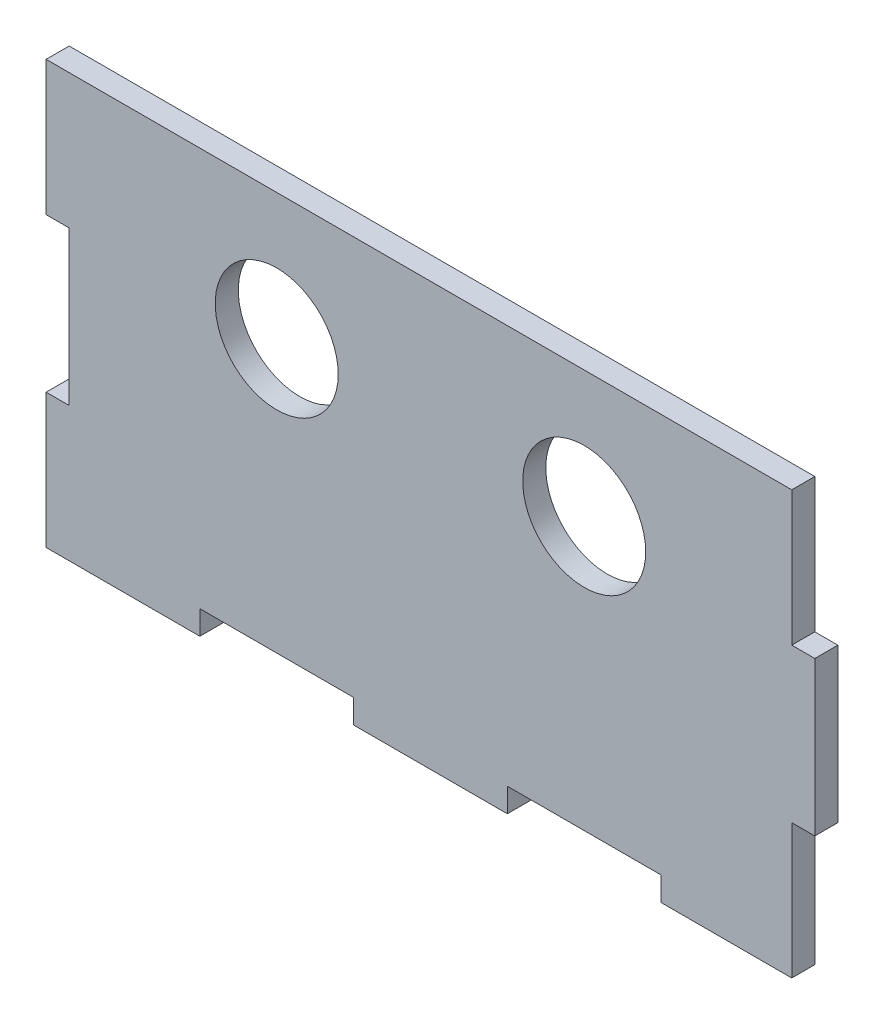
SolidWorks part; units mm, degrees
ref_plane "Front Plane" through (0, 0, 0) normal (0, 0, 1) x (1, 0, 0)
ref_plane "Top Plane" through (0, 0, 0) normal (0, 1, 0) x (1, 0, 0)
ref_plane "Right Plane" through (0, 0, 0) normal (1, 0, 0) x (0, 0, -1)
sketch "Sketch1" plane through (0, 0, 0) normal (0, 0, 1) x (1, 0, 0)
  line L0 (-50, -27.5) -> (-50, -10)
  line L1 (-50, -27.5) -> (50, -27.5)
  line L2 (-50, -27.5) -> (-50, 27.5)
  line L3 (-50, 27.5) -> (50, 27.5)
  line L4 (50, -27.5) -> (50, 27.5)
  line L5 (-50, -27.5) -> (50, 27.5) construction
  line L6 (-50, 27.5) -> (50, -27.5) construction
  line L7 (-50, -10) -> (-47, -10)
  line L8 (-47, -10) -> (-47, 10)
  line L9 (-47, 10) -> (-50, 10)
  line L10 (-50, 10) -> (-50, 27.5)
  line L11 (50, -10) -> (47, -10)
  line L12 (47, -10) -> (47, -27.5)
  line L13 (50, 10) -> (47, 10)
  line L14 (47, 10) -> (47, 27.5)
  line L15 (-50, -27.5) -> (-30, -27.5)
  line L16 (-30, -27.5) -> (-30, -24.3935)
  line L17 (-30, -24.3935) -> (-10, -24.3935)
  line L18 (-10, -24.3935) -> (-10, -27.5)
  line L19 (-10, -27.5) -> (10, -27.5)
  line L20 (10, -27.5) -> (10, -24.3935)
  line L21 (10, -24.3935) -> (30, -24.3935)
  line L22 (30, -24.3935) -> (30, -27.5)
  circle A0 centre (-20, 11) radius 8
  circle A1 centre (20, 11) radius 8
  point P0 (0, 0)
  dimension "D12" = 16
  dimension "D15" = 16
  dimension "D1" = 55
  dimension "D2" = 17.5
  dimension "D3" = 17.5
  dimension "D4" = 3
  dimension "D5" = 3
  dimension "D6" = 3
  dimension "D7" = 100
  dimension "D8" = 20
  dimension "D9" = 20
  dimension "D10" = 20
  dimension "D11" = 20
  dimension "D13" = 30
  dimension "D14" = 16.5
  dimension "D16" = 16.5
  dimension "D17" = 30
extrude "Boss-Extrude1" add sketch "Sketch1" along normal blind 3 contours L13 L14 L3 L2 L9 L8 L7 L0 L1 L12 L11 L4
